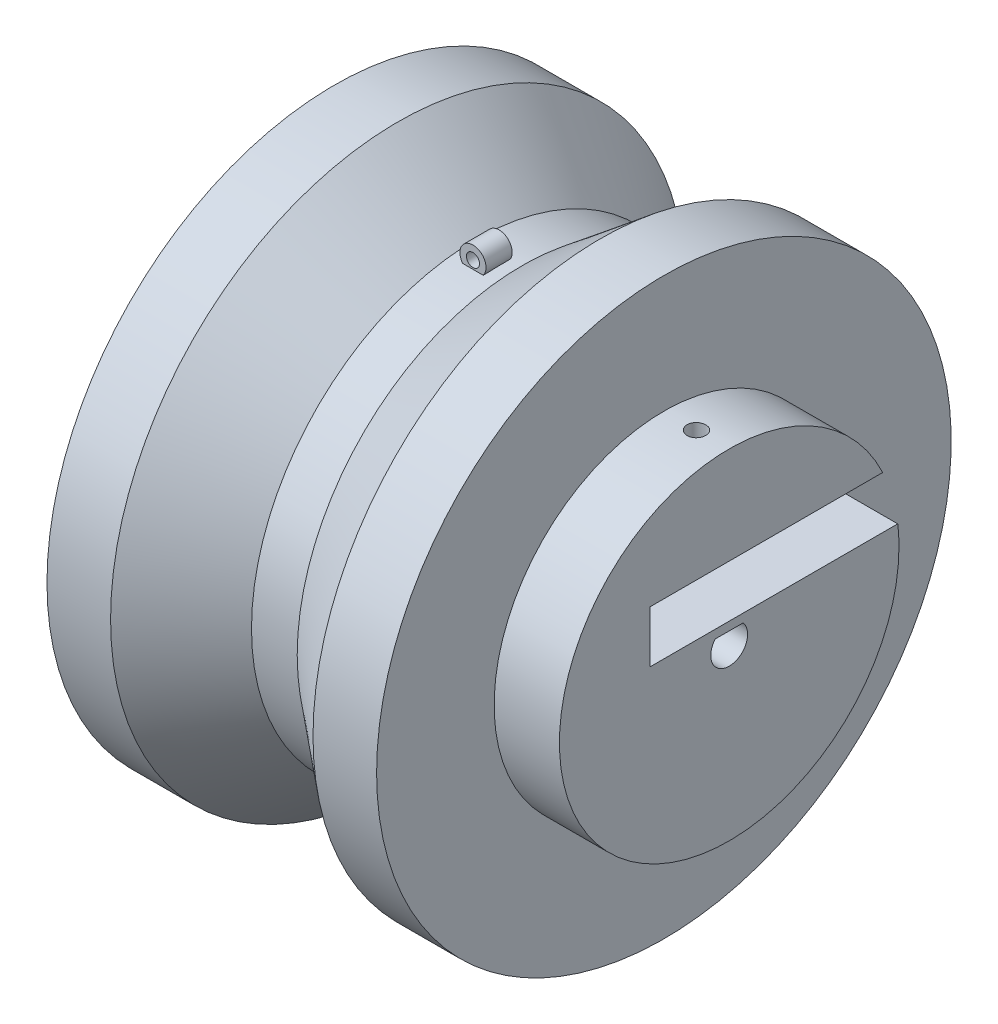
SolidWorks part; units mm, degrees
ref_plane "前基準面" through (0, 0, 0) normal (0, 0, 1) x (1, 0, 0)
ref_plane "上基準面" through (0, 0, 0) normal (0, 1, 0) x (1, 0, 0)
ref_plane "右基準面" through (0, 0, 0) normal (1, 0, 0) x (0, 0, -1)
sketch "草圖1" plane through (0, 0, 0) normal (0, 0, 1) x (1, 0, 0)
  line L0 (0, 0) -> (0, 44)
  line L1 (0, 44) -> (9.74, 44)
  line L2 (9.74, 44) -> (21.74, 34.4189)
  line L3 (21.74, 34.4189) -> (28.74, 34.4189)
  line L4 (28.74, 34.4189) -> (40.74, 44)
  line L5 (40.74, 44) -> (50.48, 44)
  line L6 (50.48, 44) -> (50.48, 34.4189)
  line L7 (50.48, 34.4189) -> (60.48, 34.4189)
  line L8 (60.48, 34.4189) -> (60.48, 0)
  line L9 (-743.1564, 0) -> (36475.4845, 0) construction
  line L10 (0, 0) -> (60.48, 0)
  dimension "D1" = 44
  dimension "D2" = 9.74
  dimension "D3" = 12
  dimension "D4" = 7
  dimension "D5" = 12
  dimension "D6" = 9.74
  dimension "D7" = 10
revolve "旋轉1" add sketch "草圖1" angle 360 about L9
ref_plane "平面1" through (0, 12, 0) normal (0, 1, 0) x (1, 0, 0)
sketch "草圖3" plane through (60.48, 0, 0) normal (1, 0, 0) x (0, 0, -1)
  circle A0 centre (0, 0) radius 2.825
  dimension "D1" = 5.65
extrude "除料-伸長2" cut sketch "草圖3" against normal blind 35
ref_plane "平面2" through (0, 22, 0) normal (0, 1, 0) x (1, 0, 0)
sketch "草圖16" plane through (60.48, 0, 0) normal (1, 0, 0) x (0, 0, -1)
  line L1 (-2.61, 2.851) -> (2.3989, 2.851)
  line L2 (-2.61, 2.851) -> (-2.61, 1.851)
  line L3 (-2.61, 1.851) -> (2.3989, 1.851)
  line L4 (2.3989, 2.851) -> (2.3989, 1.851)
  dimension "D1" = 1
extrude "填料-伸長2" add sketch "草圖16" against normal blind 30
sketch "草圖19" plane through (60.48, 0, 0) normal (1, 0, 0) x (0, 0, -1)
  line L1 (-0.5637, 2.9297) -> (0.3954, 2.9297)
  line L2 (-0.5637, 2.9297) -> (-0.5637, 2.4182)
  line L3 (-0.5637, 2.4182) -> (0.3954, 2.4182)
  line L4 (0.3954, 2.9297) -> (0.3954, 2.4182)
extrude "填料-伸長3" add sketch "草圖19" against normal blind 30
sketch "草圖24" plane through (60.48, 0, 0) normal (1, 0, 0) x (0, 0, -1)
  line L1 (-12.1511, 11.1092) -> (33.6767, 11.1092)
  line L2 (-12.1511, 11.1092) -> (-12.1511, 7.1092)
  line L3 (-12.1511, 7.1092) -> (33.6767, 7.1092)
  line L4 (33.6767, 11.1092) -> (33.6767, 7.1092)
  line L5 (-12.1511, 11.1092) -> (33.6767, 7.1092) construction
  line L6 (-12.1511, 7.1092) -> (33.6767, 11.1092) construction
  circle A0 centre (0, 0) radius 34.4189 construction
  point P0 (10.7628, 9.1092)
  dimension "D1" = 4
extrude "除料-伸長8" cut sketch "草圖24" against normal blind 9
sketch "草圖25" plane through (0, 22, 0) normal (0, 1, 0) x (1, 0, 0)
  circle A0 centre (29.9567, 0) radius 1.43
  dimension "D1" = 2.86
extrude "除料-伸長9" cut sketch "草圖25" against normal blind 22
ref_plane "平面4" through (0, 0, 0) normal (0, 0, 1) x (1, 0, 0)
sketch "草圖27" plane through (0, 0, 0) normal (0, 0, 1) x (1, 0, 0)
  line L0 (25.24, -965.5811) -> (25.24, 49034.4189) construction
  line L1 (28.74, 34.4189) -> (21.74, 34.4189) construction
  circle A0 centre (25.24, 35.4189) radius 1
  point P5 (25.24, 34.4189)
  dimension "D1" = 2
  dimension "D2" = 1
extrude "伸長-薄件2" add sketch "草圖27" along normal blind 4 thin
ref_plane "平面5" through (0, 35, 0) normal (0, 1, 0) x (1, 0, 0)
sketch "草圖28" plane through (0, 35, 0) normal (0, 1, 0) x (1, 0, 0)
  line L0 (55.48, -1034.4189) -> (55.48, 48965.5811) construction
  line L1 (50.48, -34.4189) -> (60.48, -34.4189) construction
  circle A0 centre (55.48, 0) radius 1.43
  point P5 (55.48, -34.4189)
  dimension "D1" = 2.86
extrude "除料-伸長11" cut sketch "草圖28" against normal blind 25
sketch "草圖29" plane through (0, 0, 0) normal (0, 0, 1) x (1, 0, 0)
  line L1 (60.48, 7.1092) -> (51.48, 7.1092)
  line L2 (60.48, 7.1092) -> (60.48, 3.1485)
  line L3 (60.48, 3.1485) -> (51.48, 3.1485)
  line L4 (51.48, 7.1092) -> (51.48, 3.1485)
extrude "除料-伸長12" cut sketch "草圖29" against normal blind 35 and the other way blind 12.15
sketch "草圖30" plane through (60.48, 0, 0) normal (1, 0, 0) x (0, 0, -1)
  line L0 (-1034.4189, 0) -> (48965.5811, 0) construction
  line L1 (0, -965.5811) -> (0, 49034.4189) construction
  circle A4 centre (0, 0) radius 26
  dimension "D1" = 52
extrude "除料-伸長-薄件1" cut sketch "草圖30" against normal blind 10 thin
